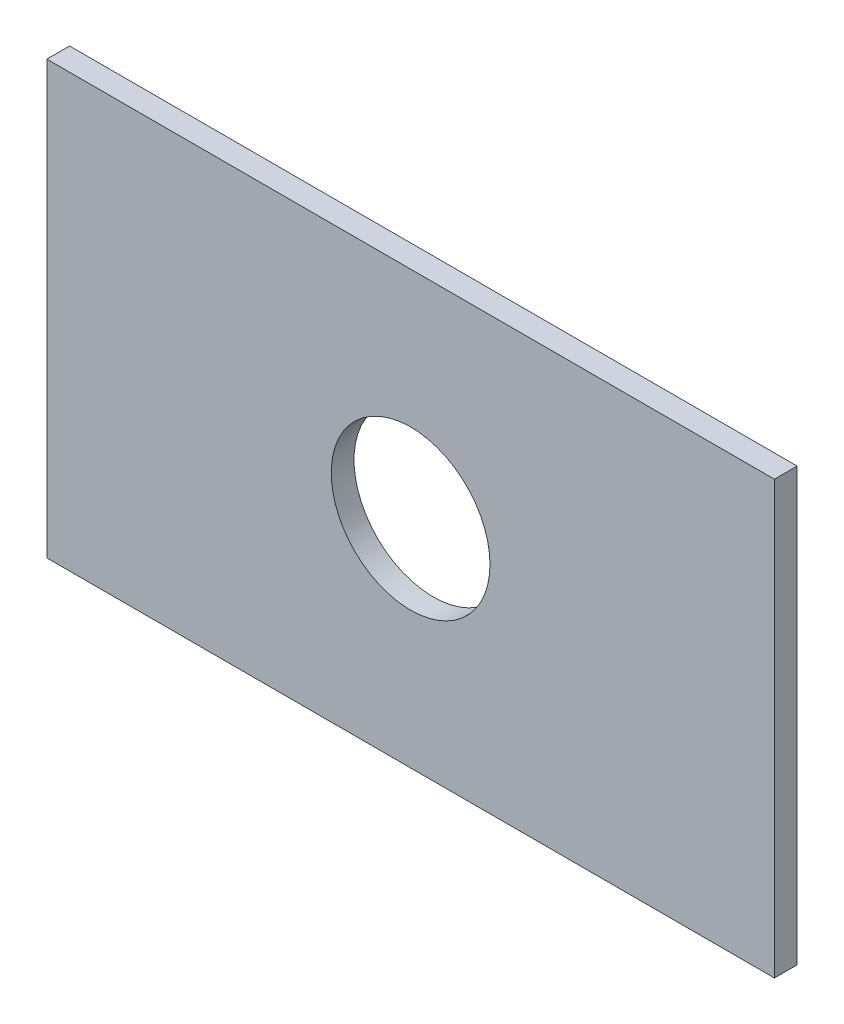
SolidWorks part; units mm, degrees
material "Cast Alloy Steel"
ref_plane "Front Plane" through (0, 0, 0) normal (0, 0, 1) x (1, 0, 0)
ref_plane "Top Plane" through (0, 0, 0) normal (0, 1, 0) x (1, 0, 0)
ref_plane "Right Plane" through (0, 0, 0) normal (1, 0, 0) x (0, 0, -1)
sketch "BlockBase" plane through (0, 0, 0) normal (0, 0, 1) x (1, 0, 0)
  line L1 (-101.6, -60.325) -> (101.6, -60.325)
  line L2 (-101.6, -60.325) -> (-101.6, 60.325)
  line L3 (-101.6, 60.325) -> (101.6, 60.325)
  line L4 (101.6, -60.325) -> (101.6, 60.325)
  line L5 (-101.6, -60.325) -> (101.6, 60.325) construction
  line L6 (-101.6, 60.325) -> (101.6, -60.325) construction
  point P0 (0, 0)
  dimension "Length" = 203.2
  dimension "Width" = 120.65
extrude "Block" add sketch "BlockBase" along normal blind 6.35
sketch "Sketch1" plane through (0, 0, 6.35) normal (0, 0, 1) x (1, 0, 0)
  circle A0 centre (0, 0) radius 22.1659
extrude "Cut-Extrude1" cut sketch "Sketch1" against normal through all
